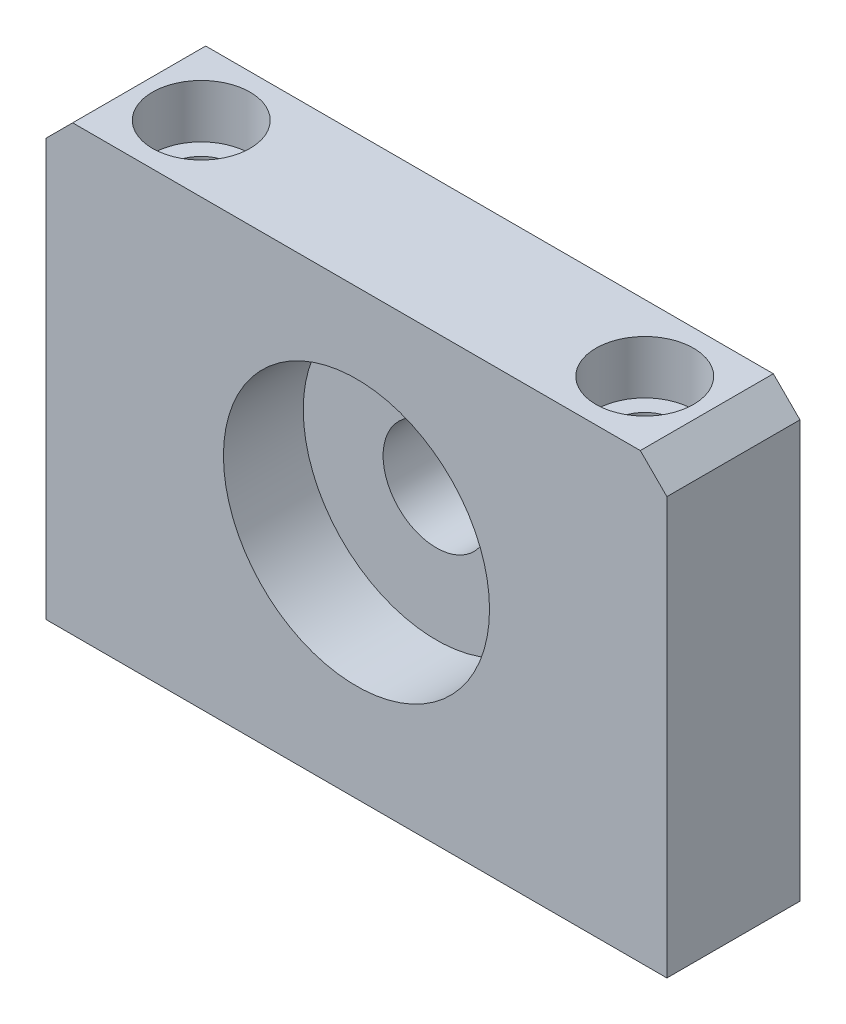
SolidWorks part; units mm, degrees
material "SKD11淬火HRC56-60"
ref_plane "前基準面" through (0, 0, 0) normal (0, 0, 1) x (1, 0, 0)
ref_plane "上基準面" through (0, 0, 0) normal (0, 1, 0) x (1, 0, 0)
ref_plane "右基準面" through (0, 0, 0) normal (1, 0, 0) x (0, 0, -1)
sketch "草图1" plane through (0, 0, 0) normal (0, 0, 1) x (1, 0, 0)
  line L1 (0, 0) -> (70, 0)
  line L2 (0, 0) -> (0, 50)
  line L3 (0, 50) -> (70, 50)
  line L4 (70, 0) -> (70, 50)
  dimension "D1" = 70
  dimension "D2" = 50
extrude "凸台-拉伸1" add sketch "草图1" along normal blind 15
sketch "草图2" plane through (0, 0, 15) normal (0, 0, 1) x (1, 0, 0)
  line L0 (35, 0) -> (35, 50) construction
  line L1 (0, 0) -> (70, 0) construction
  line L2 (70, 50) -> (0, 50) construction
  circle A0 centre (35, 26) radius 6
  dimension "D1" = 26
  dimension "D2" = 12
extrude "切除-拉伸1" cut sketch "草图2" against normal through all
chamfer "倒角1" distance 3 angle 45 2 edges at (70, 50, 7.5) (0, 50, 7.5)
hole_wizard "M6 六角凹头螺钉的柱形沉头孔1" positions "草图4" profile "草图3" counterbore size "M6" standard "ISO" end condition through all
sketch "草图4" plane through (0, 50, 0) normal (0, 1, 0) x (-1, 0, 0)
  line L0 (-35, 0) -> (-35, 15) construction
  line L1 (-67, 0) -> (-3, 0) construction
  line L2 (-67, 15) -> (-3, 15) construction
  line L3 (-3, 7.5) -> (-67, 7.5) construction
  line L4 (-67, 15) -> (-67, 0) construction
  line L5 (-3, 0) -> (-3, 15) construction
  point P0 (-10, 7.5)
  point P1 (-60, 7.5)
  dimension "D1" = 50
sketch "草图3" plane through (10, 50, 7.5) normal (1, 0, 0) x (0, 0, 1)
  line L0 (0, 0) -> (0, 50)
  line L1 (0, 50) -> (3.5, 50)
  line L3 (3.5, 50) -> (3.5, 6)
  line L4 (3.5, 6) -> (5.5, 6)
  line L5 (5.5, 6) -> (5.5, 0)
  line L7 (5.5, 0) -> (0, 0)
  line L11 (0, -6.35) -> (0, 107.95) construction
  dimension "通孔孔直径" = 7
  dimension "通孔孔深度" = 50
  dimension "柱形沉头孔直径" = 11
  dimension "柱形沉头孔深度" = 6
sketch "草图5" plane through (0, 0, 15) normal (0, 0, 1) x (1, 0, 0)
  circle A0 centre (35, 26) radius 15
  dimension "D1" = 30
extrude "切除-拉伸2" cut sketch "草图5" against normal blind 9
